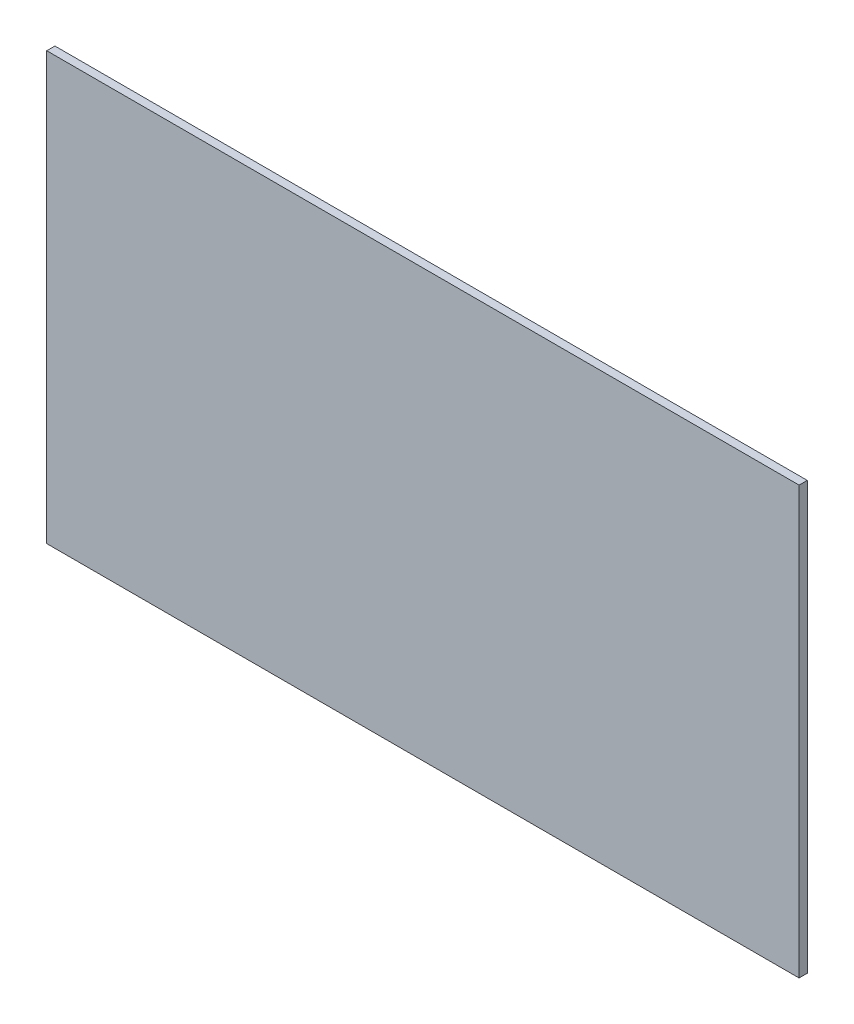
SolidWorks part; units mm, degrees
ref_plane "정면" through (0, 0, 0) normal (0, 0, 1) x (1, 0, 0)
ref_plane "윗면" through (0, 0, 0) normal (0, 1, 0) x (1, 0, 0)
ref_plane "우측면" through (0, 0, 0) normal (1, 0, 0) x (0, 0, -1)
sketch "스케치1" plane through (0, 0, 0) normal (0, 0, 1) x (1, 0, 0)
  line L1 (-230, 130.5) -> (230, 130.5)
  line L2 (-230, 130.5) -> (-230, -130.5)
  line L3 (-230, -130.5) -> (230, -130.5)
  line L4 (230, 130.5) -> (230, -130.5)
  line L5 (-230, 130.5) -> (230, -130.5) construction
  line L6 (-230, -130.5) -> (230, 130.5) construction
  point P0 (0, 0)
  dimension "D1" = 261
  dimension "D2" = 460
extrude "보스-돌출1" add sketch "스케치1" along normal blind 5
